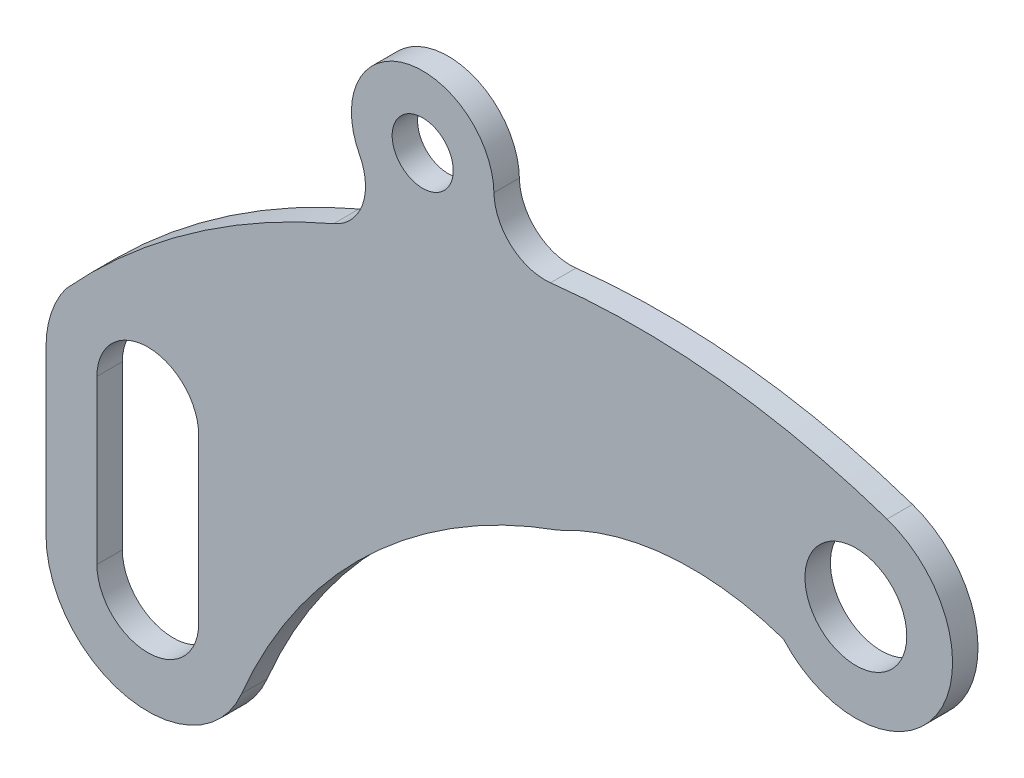
SolidWorks part; units mm, degrees
ref_plane "Front Plane" through (0, 0, 0) normal (0, 0, 1) x (1, 0, 0)
ref_plane "Top Plane" through (0, 0, 0) normal (0, 1, 0) x (1, 0, 0)
ref_plane "Right Plane" through (0, 0, 0) normal (1, 0, 0) x (0, 0, -1)
sketch "Sketch1" plane through (0, 0, 0) normal (0, 0, 1) x (1, 0, 0)
  line L0 (0, 0) -> (0, 27.7298) construction
  line L1 (0, 0) -> (0, -6) construction
  line L2 (0, 0) -> (-30.7229, 0) construction
  line L3 (0, 0) -> (42.0985, 0) construction
  line L4 (0, 27.7298) -> (85.0985, 27.7298) construction
  line L5 (42.0985, 0) -> (42.0985, -34.6465) construction
  line L6 (42.0985, -34.6465) -> (42.0985, -46.6264) construction
  line L7 (85.0985, 27.7298) -> (85.0985, -34.6465) construction
  line L8 (42.0985, -34.6465) -> (85.0985, -34.6465) construction
  line L9 (85.0985, -53.6465) -> (85.0985, -54.5786) construction
  line L10 (85.0985, -34.6465) -> (85.0985, -44.6465) construction
  line L11 (85.0985, -102) -> (-54, -102) construction
  line L12 (49.0985, -102) -> (49.0985, -112) construction
  line L13 (49.0985, -112) -> (85.0985, -112) construction
  line L14 (-54, -92) -> (-54, -70) construction
  line L15 (-34, -70) -> (-34, -102)
  line L16 (-74, -70) -> (-74, -102)
  line L17 (-64, -70) -> (-64, -102)
  line L18 (-44, -70) -> (-44, -102)
  line L19 (0, -14) -> (0, -25.265) construction
  circle A0 centre (0, 0) radius 6
  arc A1 (0, -14) -> (3.5602, -13.5398) centre (0, 0) ccw
  circle A2 centre (85.0985, -34.6465) radius 10
  circle A3 centre (85.0985, -34.6465) radius 19
  arc A4 (91.2249, -16.6613) -> (-70.0585, -58.0784) centre (42.2136, -160.5429) ccw
  arc A5 (13.9978, 0.2506) -> (25.1207, -9.507) centre (23.9962, 0.4296) ccw
  arc A6 (-64, -102) -> (-44, -102) centre (-54, -102) ccw
  arc A7 (-74, -102) -> (-34, -102) centre (-54, -102) ccw
  arc A8 (-44, -70) -> (-64, -70) centre (-54, -70) ccw
  arc A11 (-17.5052, -20.7657) -> (-12.4084, -6.4833) centre (-21.5635, -11.2668) ccw
  arc A12 (63.3341, -45.2314) -> (57.5021, -44.806) centre (58.6118, -69.7813) ccw
  arc A14 (85.0985, -54.5786) -> (83.6753, -53.5931) centre (52.8782, -99.5892) ccw
  arc A15 (60.1949, -44.7206) -> (57.5021, -44.806) centre (62.2074, -150.7015) ccw
  arc A16 (70.8729, -47.2414) -> (26.6494, -50.8435) centre (52.8782, -99.5892) ccw
  arc A17 (26.6494, -50.8435) -> (-35.5544, -109.7304) centre (62.2074, -150.7015) ccw
  arc A18 (14, 0) -> (-12.4084, -6.4833) centre (0, 0) ccw
  arc A20 (-34, -70) -> (-74, -70) centre (-54, -70) ccw
  point P41 (0, 0)
  point P45 (51.1804, -108.4158)
extrude "Boss-Extrude5" add sketch "Sketch1" along normal blind 5
